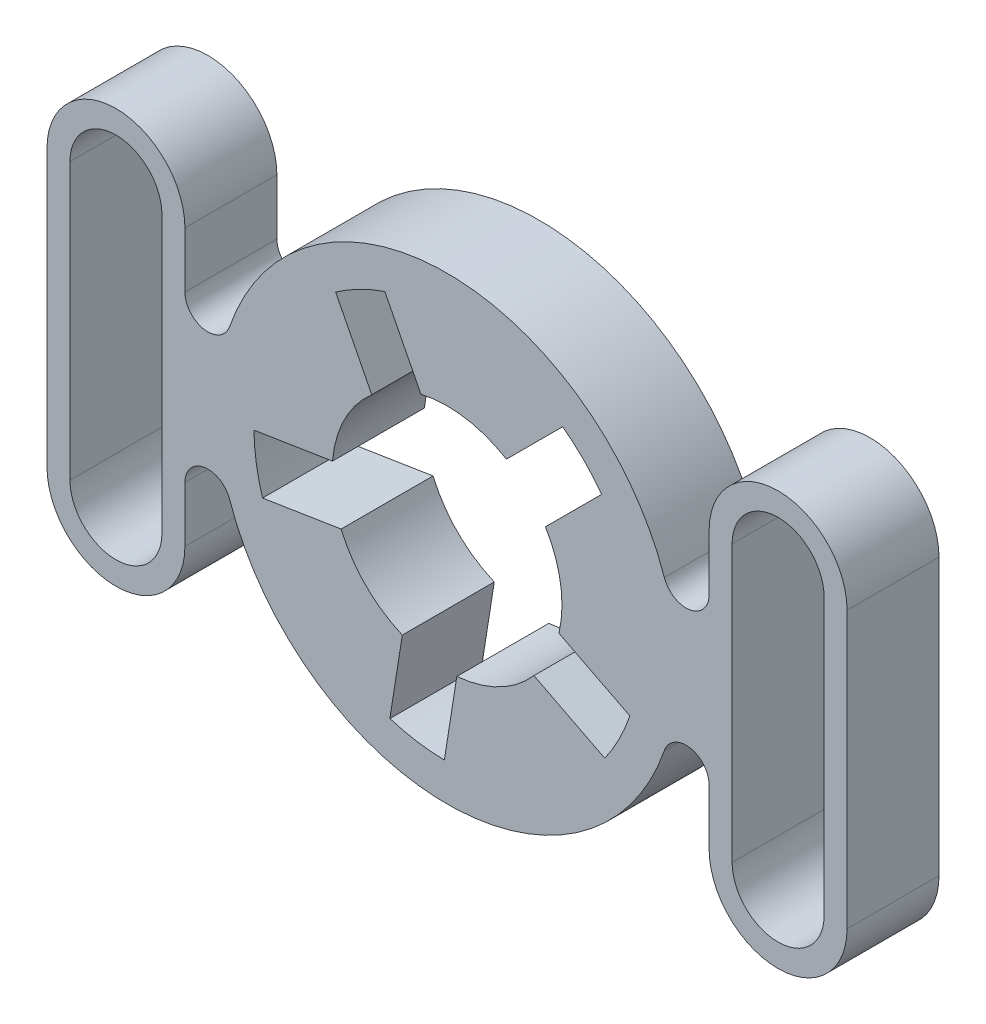
SolidWorks part; units mm, degrees
material "Wrought Stainless Steel"
ref_plane "Front Plane" through (0, 0, 0) normal (0, 0, 1) x (1, 0, 0)
ref_plane "Top Plane" through (0, 0, 0) normal (0, 1, 0) x (1, 0, 0)
ref_plane "Right Plane" through (0, 0, 0) normal (1, 0, 0) x (0, 0, -1)
sketch "Sketch1" plane through (0, 0, 0) normal (0, 0, 1) x (1, 0, 0)
  line L0 (0, 0) -> (0, 50000) construction
  line L1 (0, 0) -> (35355.3391, 35355.3391) construction
  line L2 (33.6365, 25.1512) -> (21.4036, 12.9184)
  line L3 (25.1512, 33.6365) -> (12.9184, 21.4036)
  line L4 (34.3145, -24.2181) -> (18.9002, -16.3641)
  line L5 (39.7624, -13.526) -> (24.3481, -5.672)
  line L6 (-12.429, -40.1188) -> (-9.7227, -23.0319)
  line L7 (-0.5767, -41.996) -> (2.1296, -24.9091)
  line L8 (-41.996, -0.5767) -> (-24.9091, 2.1296)
  line L9 (-40.1188, -12.429) -> (-23.0319, -9.7227)
  line L10 (-13.526, 39.7624) -> (-5.672, 24.3481)
  line L11 (-24.2181, 34.3145) -> (-16.3641, 18.9002)
  line L12 (72, 30) -> (72, -30) construction
  line L13 (87, 30) -> (87, -30)
  line L14 (57, 30) -> (57, 17.9165)
  line L15 (72, 30) -> (72, -30) construction
  line L16 (82, 30) -> (82, -30)
  line L17 (62, 30) -> (62, -30)
  line L18 (-72, 30) -> (-72, -30) construction
  line L19 (-87, 30) -> (-87, -30)
  line L20 (-57, 30) -> (-57, 17.9165)
  line L21 (-72, 30) -> (-72, -30) construction
  line L22 (-82, 30) -> (-82, -30)
  line L23 (-62, 30) -> (-62, -30)
  line L24 (-57, -17.9165) -> (-57, -30)
  line L25 (57, -17.9165) -> (57, -30)
  circle A0 centre (0, 0) radius 15
  circle A1 centre (0, 0) radius 25
  circle A2 centre (0, 0) radius 42 construction
  arc A3 (-47.2727, -16.2877) -> (47.2727, -16.2877) centre (0, 0) ccw
  arc A4 (33.6365, 25.1512) -> (25.1512, 33.6365) centre (0, 0) ccw
  arc A5 (-13.526, 39.7624) -> (-24.2181, 34.3145) centre (0, 0) ccw
  arc A6 (-41.996, -0.5767) -> (-40.1188, -12.429) centre (0, 0) ccw
  arc A7 (-12.429, -40.1188) -> (0, -42) centre (0, 0) ccw
  arc A8 (34.3145, -24.2181) -> (39.7624, -13.526) centre (0, 0) ccw
  arc A9 (87, 30) -> (57, 30) centre (72, 30) ccw
  arc A10 (57, -30) -> (87, -30) centre (72, -30) ccw
  arc A11 (82, 30) -> (62, 30) centre (72, 30) ccw
  arc A12 (62, -30) -> (82, -30) centre (72, -30) ccw
  arc A13 (57, 17.9165) -> (47.2727, 16.2877) centre (52, 17.9165) cw
  arc A14 (57, -17.9165) -> (47.2727, -16.2877) centre (52, -17.9165) ccw
  arc A15 (-87, 30) -> (-57, 30) centre (-72, 30) cw
  arc A16 (-57, -30) -> (-87, -30) centre (-72, -30) cw
  arc A17 (-82, 30) -> (-62, 30) centre (-72, 30) cw
  arc A18 (-62, -30) -> (-82, -30) centre (-72, -30) cw
  arc A19 (-57, -17.9165) -> (-47.2727, -16.2877) centre (-52, -17.9165) cw
  arc A20 (-57, 17.9165) -> (-47.2727, 16.2877) centre (-52, 17.9165) ccw
  arc A21 (47.2727, 16.2877) -> (-47.2727, 16.2877) centre (0, 0) ccw
  point P7 (0, 0)
  point P16 (27.5201, 19.0348)
  point P34 (0, 0)
  point P35 (72, 0)
  point P41 (72, 0)
  point P55 (-72, 0)
  point P62 (-72, 0)
  point P73 (0, 0)
  point P74 (0, 0)
  point P75 (0, 0)
  point P76 (0, 0)
  point P77 (0, 0)
  point P78 (0, 0)
  point P79 (0, 0)
  dimension "D1" = 30
  dimension "D2" = 50
  dimension "D3" = 84
  dimension "D4" = 100
  dimension "D8" = 84
  dimension "D11" = 15
  dimension "D12" = 10
  dimension "D13" = 5
  dimension "D14" = 30
  dimension "D15" = 15
  dimension "D16" = 15
  dimension "D5" = 45
  dimension "D6" = 12
  dimension "D9" = 72
  dimension "D10" = 60
  dimension "D17" = 30
  dimension "D18" = 60
  dimension "D7" = 5
extrude "Boss-Extrude1" add sketch "Sketch1" along normal mid plane 20
